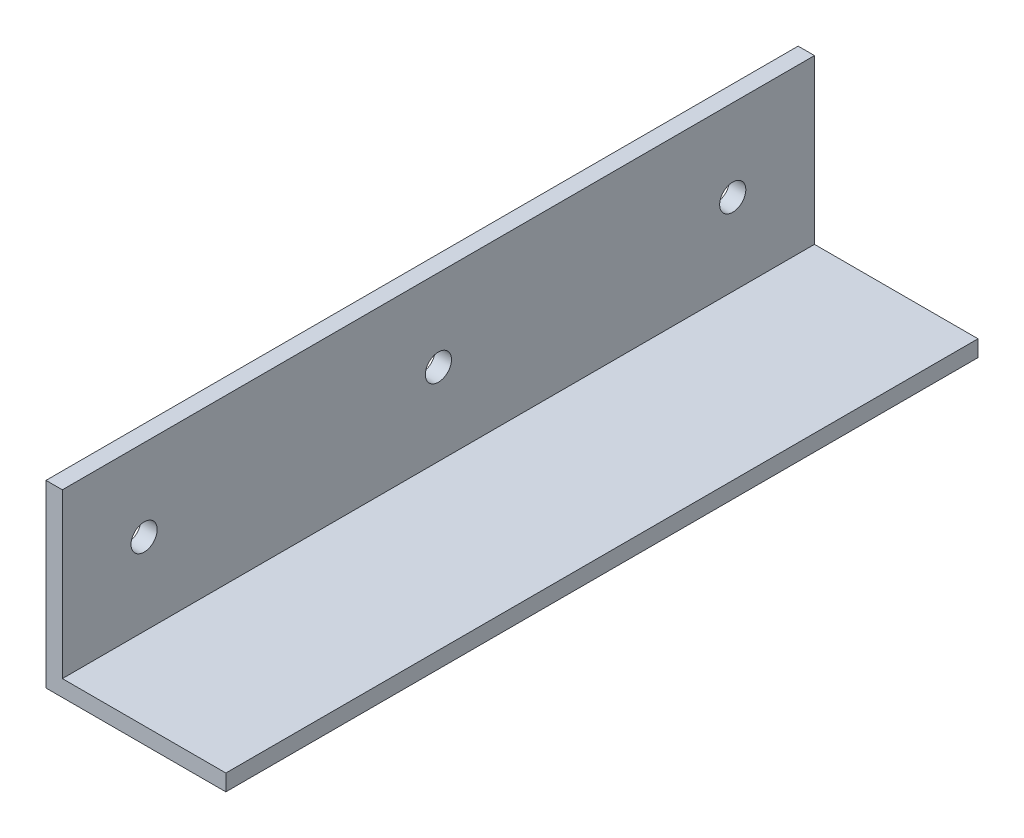
SolidWorks part; units mm, degrees
ref_plane "Front Plane" through (0, 0, 0) normal (0, 0, 1) x (1, 0, 0)
ref_plane "Top Plane" through (0, 0, 0) normal (0, 1, 0) x (1, 0, 0)
ref_plane "Right Plane" through (0, 0, 0) normal (1, 0, 0) x (0, 0, -1)
sketch "Sketch1" plane through (0, 0, 0) normal (0, 0, 1) x (1, 0, 0)
  line L2 (0, 0) -> (0, 50)
  line L3 (0, 50) -> (-5, 50)
  line L4 (-5, 0) -> (-5, 50)
  line L5 (0, 0) -> (50, 0)
  line L6 (-5, 0) -> (-5, -5)
  line L7 (-5, -5) -> (50, -5)
  line L8 (50, 0) -> (50, -5)
  dimension "D1" = 50
  dimension "D2" = 5
  dimension "D3" = 5
  dimension "D4" = 50
extrude "Boss-Extrude1" add sketch "Sketch1" along normal blind 230
sketch "Sketch2" plane through (0, 0, 0) normal (1, 0, 0) x (0, 0, -1)
  line L0 (-230, 0) -> (-230, 50) construction
  line L1 (-230, 50) -> (0, 50) construction
  circle A0 centre (-115, 25) radius 4
  circle A1 centre (-25, 25) radius 4
  circle A2 centre (-205, 25) radius 4
  dimension "D1" = 8
  dimension "D2" = 90
  dimension "D3" = 90
  dimension "D4" = 25
  dimension "D5" = 25
  dimension "D6" = 25
  dimension "D7" = 25
extrude "Cut-Extrude1" cut sketch "Sketch2" against normal through all
